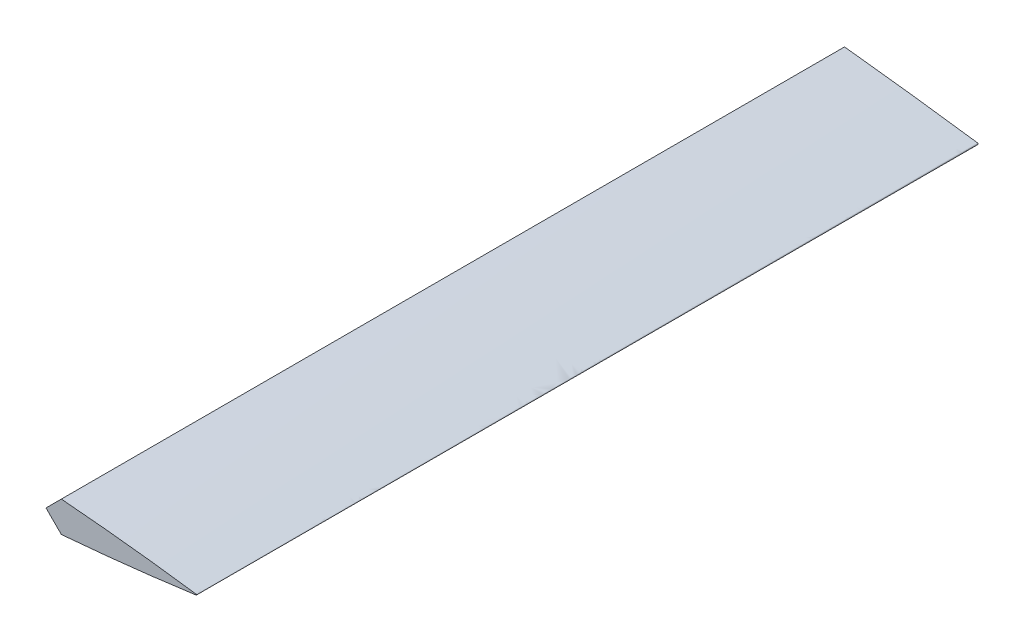
SolidWorks part; units mm, degrees
ref_plane "Front Plane" through (0, 0, 0) normal (1, 0, 0) x (0, 1, 0)
ref_plane "Top Plane" through (0, 0, 0) normal (0, 0, 1) x (0, 1, 0)
ref_plane "Right Plane" through (0, 0, 0) normal (0, 1, 0) x (-1, 0, 0)
curve "Curve1"
  spline degree 3 poles (120, 0.1512, 0) (119.9384, 0.1598, 0) (119.6921, 0.1944, 0) (119.1396, 0.2714, 0) (118.2224, 0.3987, 0) (116.9463, 0.5734, 0) (115.3191, 0.7934, 0) (113.3509, 1.0543, 0) (111.0537, 1.3526, 0) (108.4418, 1.6836, 0) (105.5312, 2.0429, 0) (102.3399, 2.4251, 0) (98.8876, 2.8257, 0) (95.1955, 3.2391, 0) (91.2864, 3.6604, 0) (87.1844, 4.0843, 0) (82.9149, 4.5053, 0) (78.504, 4.9175, 0) (73.9791, 5.3155, 0) (69.368, 5.6926, 0) (64.6991, 6.0428, 0) (60.0013, 6.3594, 0) (55.3033, 6.6359, 0) (50.6343, 6.8653, 0) (46.023, 7.0415, 0) (41.4977, 7.1587, 0) (37.0863, 7.2112, 0) (32.8161, 7.1949, 0) (28.7132, 7.1065, 0) (24.8031, 6.9438, 0) (21.1096, 6.7064, 0) (17.6556, 6.3951, 0) (14.4622, 6.0122, 0) (11.5488, 5.561, 0) (8.9331, 5.0463, 0) (6.6304, 4.4738, 0) (4.6538, 3.8491, 0) (3.0134, 3.1781, 0) (1.7143, 2.4652, 0) (0.7586, 1.7091, 0) (0.1465, 0.8915, 0) (-0.0683, 0, 0) (0.1465, -0.8915, 0) (0.7586, -1.7091, 0) (1.7143, -2.4652, 0) (3.0134, -3.1781, 0) (4.6538, -3.8491, 0) (6.6304, -4.4738, 0) (8.9331, -5.0463, 0) (11.5488, -5.561, 0) (14.4622, -6.0122, 0) (17.6556, -6.3951, 0) (21.1096, -6.7064, 0) (24.8031, -6.9438, 0) (28.7132, -7.1065, 0) (32.8161, -7.1949, 0) (37.0863, -7.2112, 0) (41.4977, -7.1587, 0) (46.023, -7.0415, 0) (50.6343, -6.8653, 0) (55.3033, -6.6359, 0) (60.0013, -6.3594, 0) (64.6991, -6.0428, 0) (69.368, -5.6926, 0) (73.9791, -5.3155, 0) (78.504, -4.9175, 0) (82.9149, -4.5053, 0) (87.1844, -4.0843, 0) (91.2864, -3.6604, 0) (95.1955, -3.2391, 0) (98.8876, -2.8257, 0) (102.3399, -2.4251, 0) (105.5312, -2.0429, 0) (108.4418, -1.6836, 0) (111.0537, -1.3526, 0) (113.3509, -1.0543, 0) (115.3191, -0.7934, 0) (116.9463, -0.5734, 0) (118.2224, -0.3987, 0) (119.1396, -0.2714, 0) (119.6921, -0.1944, 0) (119.9384, -0.1598, 0) (120, -0.1512, 0) knots 0 0 0 0 0.000763 0.003048 0.006841 0.012116 0.018841 0.026973 0.03646 0.047243 0.059254 0.072417 0.086651 0.101866 0.117969 0.134858 0.152428 0.170572 0.189175 0.208122 0.227297 0.24658 0.265853 0.284997 0.303895 0.322433 0.340499 0.357984 0.374788 0.390812 0.405965 0.420162 0.433328 0.445394 0.456301 0.466004 0.474472 0.481696 0.487704 0.492583 0.496544 0.5 0.503456 0.507417 0.512296 0.518304 0.525528 0.533996 0.543699 0.554606 0.566672 0.579838 0.594035 0.609188 0.625212 0.642016 0.659501 0.677567 0.696105 0.715003 0.734147 0.75342 0.772703 0.791878 0.810825 0.829428 0.847572 0.865142 0.882031 0.898134 0.913349 0.927583 0.940746 0.952757 0.96354 0.973027 0.981159 0.987884 0.993159 0.996952 0.999237 1 1 1 1
curve "Curve2"
  spline degree 3 poles (60, 0.0756, 0) (59.9883, 0.0772, 0) (59.9416, 0.0838, 0) (59.8367, 0.0985, 0) (59.6621, 0.1229, 0) (59.4182, 0.1568, 0) (59.1056, 0.2, 0) (58.725, 0.2522, 0) (58.2774, 0.3132, 0) (57.7637, 0.3825, 0) (57.1851, 0.4596, 0) (56.5431, 0.5442, 0) (55.839, 0.6357, 0) (55.0747, 0.7337, 0) (54.2517, 0.8375, 0) (53.3721, 0.9467, 0) (52.438, 1.0606, 0) (51.4514, 1.1787, 0) (50.4147, 1.3003, 0) (49.3304, 1.425, 0) (48.2009, 1.5521, 0) (47.0288, 1.6809, 0) (45.8171, 1.8109, 0) (44.5683, 1.9415, 0) (43.2856, 2.072, 0) (41.9718, 2.2018, 0) (40.6301, 2.3301, 0) (39.2635, 2.4565, 0) (37.8753, 2.58, 0) (36.4687, 2.7001, 0) (35.047, 2.816, 0) (33.6135, 2.927, 0) (32.1716, 3.0322, 0) (30.7246, 3.131, 0) (29.2759, 3.2225, 0) (27.8289, 3.3059, 0) (26.3869, 3.3806, 0) (24.9534, 3.4457, 0) (23.5317, 3.5004, 0) (22.1251, 3.5442, 0) (20.7368, 3.5763, 0) (19.3702, 3.5962, 0) (18.0284, 3.6032, 0) (16.7145, 3.597, 0) (15.4317, 3.5772, 0) (14.1829, 3.5434, 0) (12.971, 3.4956, 0) (11.7988, 3.4335, 0) (10.6691, 3.3571, 0) (9.5846, 3.2667, 0) (8.5477, 3.1624, 0) (7.5609, 3.0445, 0) (6.6264, 2.9134, 0) (5.7465, 2.7696, 0) (4.9231, 2.6137, 0) (4.1582, 2.4461, 0) (3.4535, 2.2677, 0) (2.8107, 2.0791, 0) (2.231, 1.8809, 0) (1.7158, 1.6738, 0) (1.2661, 1.4585, 0) (0.8827, 1.2355, 0) (0.5661, 1.0049, 0) (0.3168, 0.7666, 0) (0.1356, 0.5197, 0) (0.0247, 0.2632, 0) (-0.0121, 0, 0) (0.0247, -0.2632, 0) (0.1356, -0.5197, 0) (0.3168, -0.7666, 0) (0.5661, -1.0049, 0) (0.8827, -1.2355, 0) (1.2661, -1.4585, 0) (1.7158, -1.6738, 0) (2.231, -1.8809, 0) (2.8107, -2.0791, 0) (3.4535, -2.2677, 0) (4.1582, -2.4461, 0) (4.9231, -2.6137, 0) (5.7465, -2.7696, 0) (6.6264, -2.9134, 0) (7.5609, -3.0445, 0) (8.5477, -3.1624, 0) (9.5846, -3.2667, 0) (10.6691, -3.3571, 0) (11.7988, -3.4335, 0) (12.971, -3.4956, 0) (14.1829, -3.5434, 0) (15.4317, -3.5772, 0) (16.7145, -3.597, 0) (18.0284, -3.6032, 0) (19.3702, -3.5962, 0) (20.7368, -3.5763, 0) (22.1251, -3.5442, 0) (23.5317, -3.5004, 0) (24.9534, -3.4457, 0) (26.3869, -3.3806, 0) (27.8289, -3.3059, 0) (29.2759, -3.2225, 0) (30.7246, -3.131, 0) (32.1716, -3.0322, 0) (33.6135, -2.927, 0) (35.047, -2.816, 0) (36.4687, -2.7001, 0) (37.8753, -2.58, 0) (39.2635, -2.4565, 0) (40.6301, -2.3301, 0) (41.9718, -2.2018, 0) (43.2856, -2.072, 0) (44.5683, -1.9415, 0) (45.8171, -1.8109, 0) (47.0288, -1.6809, 0) (48.2009, -1.5521, 0) (49.3304, -1.425, 0) (50.4147, -1.3003, 0) (51.4514, -1.1787, 0) (52.438, -1.0606, 0) (53.3721, -0.9467, 0) (54.2517, -0.8375, 0) (55.0747, -0.7337, 0) (55.839, -0.6357, 0) (56.5431, -0.5442, 0) (57.1851, -0.4596, 0) (57.7637, -0.3825, 0) (58.2774, -0.3132, 0) (58.725, -0.2522, 0) (59.1056, -0.2, 0) (59.4182, -0.1568, 0) (59.6621, -0.1229, 0) (59.8367, -0.0985, 0) (59.9416, -0.0838, 0) (59.9883, -0.0772, 0) (60, -0.0756, 0) knots 0 0 0 0 0.000289 0.001156 0.002598 0.004612 0.007194 0.010336 0.014031 0.018271 0.023046 0.028343 0.03415 0.040454 0.047239 0.054489 0.062186 0.070314 0.078852 0.08778 0.097077 0.106722 0.116691 0.126961 0.137507 0.148306 0.159331 0.170557 0.181957 0.193504 0.205172 0.216932 0.228758 0.240621 0.252495 0.26435 0.276161 0.287898 0.299536 0.311047 0.322405 0.333584 0.344559 0.355306 0.3658 0.376018 0.385938 0.395538 0.404798 0.413699 0.422222 0.430349 0.438066 0.445357 0.452209 0.458611 0.464554 0.47003 0.475035 0.479569 0.483637 0.48725 0.490431 0.493219 0.495674 0.497891 0.5 0.502109 0.504326 0.506781 0.509569 0.51275 0.516363 0.520431 0.524965 0.52997 0.535446 0.541389 0.547791 0.554643 0.561934 0.569651 0.577778 0.586301 0.595202 0.604462 0.614062 0.623982 0.6342 0.644694 0.655441 0.666416 0.677595 0.688953 0.700464 0.712102 0.723839 0.73565 0.747505 0.759379 0.771242 0.783068 0.794828 0.806496 0.818043 0.829443 0.840669 0.851694 0.862493 0.873039 0.883309 0.893278 0.902923 0.91222 0.921148 0.929686 0.937814 0.945511 0.952761 0.959546 0.96585 0.971657 0.976954 0.981729 0.985969 0.989664 0.992806 0.995388 0.997402 0.998844 0.999711 1 1 1 1
sketch "Sketch3" plane through (0, 0, 0) normal (0, 0, 1) x (0, 1, 0)
  arc A0 (-0.1512, -120) -> (0.1512, -120) centre (0, -119.9788) ccw
  spline S0 degree 3 poles (1963.2865, -496.8861) (-12.8593, -186.2558) (-4.4646, -153.1098) (0.2714, -119.1396) (0.3987, -118.2224) (0.5734, -116.9463) (0.7934, -115.3191) (1.0543, -113.3509) (1.3526, -111.0537) (1.6836, -108.4418) (2.0429, -105.5312) (2.4251, -102.3399) (2.8257, -98.8876) (3.2391, -95.1955) (3.6604, -91.2864) (4.0843, -87.1844) (4.5053, -82.9149) (4.9175, -78.504) (5.3155, -73.9791) (5.6926, -69.368) (6.0428, -64.6991) (6.3594, -60.0013) (6.6359, -55.3033) (6.8653, -50.6343) (7.0415, -46.023) (7.1587, -41.4977) (7.2112, -37.0863) (7.1949, -32.8161) (7.1065, -28.7132) (6.9438, -24.8031) (6.7064, -21.1096) (6.3951, -17.6556) (6.0122, -14.4622) (5.561, -11.5488) (5.0463, -8.9331) (4.4738, -6.6304) (3.8491, -4.6538) (3.1781, -3.0134) (2.4652, -1.7143) (1.7091, -0.7586) (0.8915, -0.1465) (0, 0.0683) (-0.8915, -0.1465) (-1.7091, -0.7586) (-2.4652, -1.7143) (-3.1781, -3.0134) (-3.8491, -4.6538) (-4.4738, -6.6304) (-5.0463, -8.9331) (-5.561, -11.5488) (-6.0122, -14.4622) (-6.3951, -17.6556) (-6.7064, -21.1096) (-6.9438, -24.8031) (-7.1065, -28.7132) (-7.1949, -32.8161) (-7.2112, -37.0863) (-7.1587, -41.4977) (-7.0415, -46.023) (-6.8653, -50.6343) (-6.6359, -55.3033) (-6.3594, -60.0013) (-6.0428, -64.6991) (-5.6926, -69.368) (-5.3155, -73.9791) (-4.9175, -78.504) (-4.5053, -82.9149) (-4.0843, -87.1844) (-3.6604, -91.2864) (-3.2391, -95.1955) (-2.8257, -98.8876) (-2.4251, -102.3399) (-2.0429, -105.5312) (-1.6836, -108.4418) (-1.3526, -111.0537) (-1.0543, -113.3509) (-0.7934, -115.3191) (-0.5734, -116.9463) (-0.3987, -118.2224) (-0.2714, -119.1396) (4.4646, -153.1096) (12.8592, -186.2554) (-1963.2505, -496.8804) knots -0.413697 -0.413697 -0.413697 -0.413697 0.000763 0.003048 0.006841 0.012116 0.018841 0.026973 0.03646 0.047243 0.059254 0.072417 0.086651 0.101866 0.117969 0.134858 0.152428 0.170572 0.189175 0.208122 0.227297 0.24658 0.265853 0.284997 0.303895 0.322433 0.340499 0.357984 0.374788 0.390812 0.405965 0.420162 0.433328 0.445394 0.456301 0.466004 0.474472 0.481696 0.487704 0.492583 0.496544 0.5 0.503456 0.507417 0.512296 0.518304 0.525528 0.533996 0.543699 0.554606 0.566672 0.579838 0.594035 0.609188 0.625212 0.642016 0.659501 0.677567 0.696105 0.715003 0.734147 0.75342 0.772703 0.791878 0.810825 0.829428 0.847572 0.865142 0.882031 0.898134 0.913349 0.927583 0.940746 0.952757 0.96354 0.973027 0.981159 0.987884 0.993159 0.996952 0.999237 1.413694 1.413694 1.413694 1.413694 only from (0.1512, -120) to (-0.1512, -120) construction
  spline S1 degree 3 poles (0.1512, -120) (0.1598, -119.9384) (0.1944, -119.6921) (0.2714, -119.1396) (0.3987, -118.2224) (0.5734, -116.9463) (0.7934, -115.3191) (1.0543, -113.3509) (1.3526, -111.0537) (1.6836, -108.4418) (2.0429, -105.5312) (2.4251, -102.3399) (2.8257, -98.8876) (3.2391, -95.1955) (3.6604, -91.2864) (4.0843, -87.1844) (4.5053, -82.9149) (4.9175, -78.504) (5.3155, -73.9791) (5.6926, -69.368) (6.0428, -64.6991) (6.3594, -60.0013) (6.6359, -55.3033) (6.8653, -50.6343) (7.0415, -46.023) (7.1587, -41.4977) (7.2112, -37.0863) (7.1949, -32.8161) (7.1065, -28.7132) (6.9438, -24.8031) (6.7064, -21.1096) (6.3951, -17.6556) (6.0122, -14.4622) (5.561, -11.5488) (5.0463, -8.9331) (4.4738, -6.6304) (3.8491, -4.6538) (3.1781, -3.0134) (2.4652, -1.7143) (1.7091, -0.7586) (0.8915, -0.1465) (0, 0.0683) (-0.8915, -0.1465) (-1.7091, -0.7586) (-2.4652, -1.7143) (-3.1781, -3.0134) (-3.8491, -4.6538) (-4.4738, -6.6304) (-5.0463, -8.9331) (-5.561, -11.5488) (-6.0122, -14.4622) (-6.3951, -17.6556) (-6.7064, -21.1096) (-6.9438, -24.8031) (-7.1065, -28.7132) (-7.1949, -32.8161) (-7.2112, -37.0863) (-7.1587, -41.4977) (-7.0415, -46.023) (-6.8653, -50.6343) (-6.6359, -55.3033) (-6.3594, -60.0013) (-6.0428, -64.6991) (-5.6926, -69.368) (-5.3155, -73.9791) (-4.9175, -78.504) (-4.5053, -82.9149) (-4.0843, -87.1844) (-3.6604, -91.2864) (-3.2391, -95.1955) (-2.8257, -98.8876) (-2.4251, -102.3399) (-2.0429, -105.5312) (-1.6836, -108.4418) (-1.3526, -111.0537) (-1.0543, -113.3509) (-0.7934, -115.3191) (-0.5734, -116.9463) (-0.3987, -118.2224) (-0.2714, -119.1396) (-0.1944, -119.6921) (-0.1598, -119.9384) (-0.1512, -120) knots 0 0 0 0 0.000763 0.003048 0.006841 0.012116 0.018841 0.026973 0.03646 0.047243 0.059254 0.072417 0.086651 0.101866 0.117969 0.134858 0.152428 0.170572 0.189175 0.208122 0.227297 0.24658 0.265853 0.284997 0.303895 0.322433 0.340499 0.357984 0.374788 0.390812 0.405965 0.420162 0.433328 0.445394 0.456301 0.466004 0.474472 0.481696 0.487704 0.492583 0.496544 0.5 0.503456 0.507417 0.512296 0.518304 0.525528 0.533996 0.543699 0.554606 0.566672 0.579838 0.594035 0.609188 0.625212 0.642016 0.659501 0.677567 0.696105 0.715003 0.734147 0.75342 0.772703 0.791878 0.810825 0.829428 0.847572 0.865142 0.882031 0.898134 0.913349 0.927583 0.940746 0.952757 0.96354 0.973027 0.981159 0.987884 0.993159 0.996952 0.999237 1 1 1 1
ref_plane "Plane2" through (0, 0, 140) normal (0, 0, 1) x (0, 1, 0)
sketch "Sketch4" plane through (0, 0, 140) normal (0, 0, 1) x (0, 1, 0)
  arc A4 (-0.0756, -119.9894) -> (0.0756, -119.9894) centre (0, -119.9788) ccw
  spline S2 degree 3 poles (0.0756, -119.9894) (0.0772, -119.9778) (0.0837, -119.9311) (0.0984, -119.8261) (0.1228, -119.6515) (0.1951, -119.1314) (0.282, -118.4981) (0.3824, -117.7531) (0.4596, -117.1746) (0.5442, -116.5325) (0.6357, -115.8285) (0.7336, -115.0641) (0.8375, -114.2412) (1.0752, -112.3257) (1.3139, -110.3072) (1.552, -108.1903) (1.7266, -106.602) (1.9003, -104.9623) (2.1175, -102.8277) (2.3346, -100.5953) (2.541, -98.3209) (2.7409, -95.9803) (2.8923, -94.0775) (3.0322, -92.161) (3.1309, -90.714) (3.2224, -89.2653) (3.3059, -87.8183) (3.3805, -86.3764) (3.4456, -84.9429) (3.5004, -83.5211) (3.5442, -82.1145) (3.5763, -80.7263) (3.5961, -79.3596) (3.6032, -78.0178) (3.597, -76.704) (3.5772, -75.4211) (3.5434, -74.1723) (3.4955, -72.9604) (3.4334, -71.7882) (3.3571, -70.6586) (3.2667, -69.574) (3.1624, -68.5371) (3.0445, -67.5503) (2.9134, -66.6159) (2.7696, -65.7359) (2.6136, -64.9126) (2.4461, -64.1477) (2.2677, -63.443) (2.079, -62.8001) (1.8808, -62.2204) (1.6738, -61.7052) (1.4585, -61.2555) (1.2354, -60.8721) (1.0048, -60.5555) (0.7665, -60.3062) (0.5197, -60.125) (0.2632, -60.0142) (0, -59.9774) (-0.2633, -60.0142) (-0.5198, -60.125) (-0.7666, -60.3062) (-1.0049, -60.5555) (-1.2355, -60.8721) (-1.4586, -61.2555) (-1.6739, -61.7052) (-1.8809, -62.2204) (-2.0791, -62.8001) (-2.2678, -63.443) (-2.4462, -64.1477) (-2.6137, -64.9126) (-2.7697, -65.7359) (-2.9135, -66.6159) (-3.0446, -67.5503) (-3.1625, -68.5371) (-3.2668, -69.574) (-3.3572, -70.6586) (-3.4335, -71.7882) (-3.4956, -72.9604) (-3.5435, -74.1723) (-3.5773, -75.4211) (-3.5971, -76.704) (-3.6033, -78.0178) (-3.5962, -79.3596) (-3.5764, -80.7263) (-3.5442, -82.1145) (-3.5005, -83.5211) (-3.4457, -84.9429) (-3.3806, -86.3764) (-3.306, -87.8183) (-3.2225, -89.2653) (-3.131, -90.714) (-3.0323, -92.161) (-2.8924, -94.0775) (-2.741, -95.9803) (-2.5411, -98.3209) (-2.3346, -100.5953) (-2.077, -103.2446) (-1.8569, -105.3788) (-1.681, -107.0183) (-1.5521, -108.1903) (-1.314, -110.3072) (-1.0752, -112.3257) (-0.8375, -114.2412) (-0.7337, -115.0641) (-0.6358, -115.8285) (-0.5442, -116.5325) (-0.4597, -117.1746) (-0.3456, -118.0295) (-0.2444, -118.7744) (-0.1568, -119.4076) (-0.1229, -119.6515) (-0.0985, -119.8261) (-0.0838, -119.9311) (-0.0773, -119.9778) (-0.0756, -119.9894) knots 0 0 0 0 0.000289 0.001156 0.002598 0.004612 0.014031 0.018271 0.023046 0.028343 0.03415 0.040454 0.047239 0.054489 0.08778 0.097077 0.106722 0.126961 0.137507 0.159331 0.181957 0.193504 0.216932 0.228758 0.240621 0.252495 0.26435 0.276161 0.287898 0.299536 0.311047 0.322405 0.333584 0.344559 0.355306 0.3658 0.376018 0.385938 0.395538 0.404798 0.413699 0.422222 0.430349 0.438066 0.445357 0.452209 0.458611 0.464554 0.47003 0.475035 0.479569 0.483637 0.48725 0.490431 0.493219 0.495674 0.497891 0.5 0.502109 0.504326 0.506781 0.509569 0.51275 0.516363 0.520431 0.524965 0.52997 0.535446 0.541389 0.547791 0.554643 0.561934 0.569651 0.577778 0.586301 0.595202 0.604462 0.614062 0.623982 0.6342 0.644694 0.655441 0.666416 0.677595 0.688953 0.700464 0.712102 0.723839 0.73565 0.747505 0.759379 0.771242 0.783068 0.806496 0.818043 0.840669 0.862493 0.883309 0.893278 0.902923 0.91222 0.945511 0.952761 0.959546 0.96585 0.971657 0.976954 0.981729 0.992806 0.995388 0.997402 0.998844 0.999711 1 1 1 1
loft "Loft1" add profiles "Sketch3", "Sketch4"
sketch "Sketch5" plane through (0, 0, 0) normal (0, 0, -1) x (1, 0, 0)
  circle A0 centre (59.9788, 0) radius 3.175
  arc A2 (120, -0.1512) -> (120, 0.1512) centre (119.9788, 0) ccw
  arc A3 (120, -0.1512) -> (120, 0.1512) centre (119.9788, 0) ccw
  spline S2 degree 3 poles (2119.9475, -2119.2172) (88.467, 73.5642) (-7.4592, 9.2673) (0.7585, -1.7091) (1.7141, -2.4652) (3.0132, -3.1781) (4.6536, -3.8491) (6.6302, -4.4738) (8.9329, -5.0463) (11.5486, -5.5611) (14.4621, -6.0122) (17.6555, -6.3951) (21.1095, -6.7064) (24.803, -6.9438) (28.7131, -7.1065) (32.816, -7.1949) (37.0862, -7.2112) (41.4976, -7.1587) (46.0229, -7.0415) (50.6342, -6.8653) (55.3033, -6.6359) (60.0012, -6.3594) (64.6991, -6.0428) (69.368, -5.6926) (73.9791, -5.3155) (78.504, -4.9175) (82.9148, -4.5053) (87.1844, -4.0843) (91.2864, -3.6604) (95.1955, -3.2392) (98.8876, -2.8257) (102.3399, -2.4251) (105.5312, -2.0429) (108.4418, -1.6836) (111.0537, -1.3526) (113.3509, -1.0543) (115.3191, -0.7934) (116.9463, -0.5734) (118.2224, -0.3987) (119.1396, -0.2714) (157.9529, 5.1398) (195.7823, 15.3513) (649.9649, -2951.4825) knots -0.152784 -0.152784 -0.152784 -0.152784 0.003456 0.007417 0.012296 0.018304 0.025528 0.033996 0.043699 0.054606 0.066672 0.079838 0.094035 0.109188 0.125212 0.142016 0.159501 0.177567 0.196105 0.215003 0.234147 0.25342 0.272703 0.291878 0.310825 0.329428 0.347572 0.365142 0.382031 0.398134 0.413349 0.427583 0.440746 0.452757 0.46354 0.473027 0.481159 0.487884 0.493159 0.496952 0.499237 0.973652 0.973652 0.973652 0.973652 only from (-0.0002, 0) to (120, -0.1512)
  spline S3 degree 3 poles (461.0436, -2895.7858) (729.0476, -278.0991) (431.132, -38.6969) (104.835, 2.1364) (97.239, 3.0204) (90.903, 3.7041) (84.5629, 4.3482) (79.4875, 4.8306) (74.409, 5.2774) (70.5984, 5.5933) (66.7862, 5.8885) (62.9723, 6.1614) (59.1567, 6.4099) (55.3395, 6.6314) (51.5206, 6.8228) (47.7002, 6.9808) (43.8784, 7.1016) (40.0556, 7.1802) (36.232, 7.211) (33.0456, 7.1913) (30.4969, 7.1443) (28.5858, 7.092) (26.6753, 7.0215) (24.7656, 6.931) (22.857, 6.819) (20.95, 6.683) (19.045, 6.5208) (17.1428, 6.3292) (15.2441, 6.1046) (13.3503, 5.8421) (11.7776, 5.5867) (10.524, 5.3562) (9.5866, 5.1687) (8.6527, 4.965) (7.7227, 4.7434) (6.7981, 4.5007) (5.8799, 4.2344) (4.9705, 3.9393) (4.0729, 3.6103) (3.1916, 3.2386) (2.3358, 2.8121) (1.5185, 2.3128) (0.7755, 1.7074) (-7.7702, -9.0011) (82.4901, -76.2927) (2232.3644, 1999.1772) knots -3.429668 -3.429668 -3.429668 -3.429668 0.532086 0.56328 0.594474 0.625669 0.641266 0.67246 0.688057 0.703654 0.719251 0.734849 0.750446 0.766043 0.78164 0.797237 0.812834 0.828431 0.844029 0.859626 0.867424 0.875223 0.883021 0.89082 0.898619 0.906417 0.914216 0.922014 0.929813 0.937611 0.94541 0.949309 0.953209 0.957108 0.961007 0.964906 0.968806 0.972705 0.976604 0.980504 0.984403 0.988302 0.992201 0.996101 1.154232 1.154232 1.154232 1.154232 only from (120, 0.1512) to (-0.0002, 0)
  spline S4 degree 3 poles (-0.0002, 0) (-0.0002, -0.2834) (0.1464, -0.8915) (0.7585, -1.7091) (1.7141, -2.4652) (3.0132, -3.1781) (4.6536, -3.8491) (6.6302, -4.4738) (8.9329, -5.0463) (11.5486, -5.5611) (14.4621, -6.0122) (17.6555, -6.3951) (21.1095, -6.7064) (24.803, -6.9438) (28.7131, -7.1065) (32.816, -7.1949) (37.0862, -7.2112) (41.4976, -7.1587) (46.0229, -7.0415) (50.6342, -6.8653) (55.3033, -6.6359) (60.0012, -6.3594) (64.6991, -6.0428) (69.368, -5.6926) (73.9791, -5.3155) (78.504, -4.9175) (82.9148, -4.5053) (87.1844, -4.0843) (91.2864, -3.6604) (95.1955, -3.2392) (98.8876, -2.8257) (102.3399, -2.4251) (105.5312, -2.0429) (108.4418, -1.6836) (111.0537, -1.3526) (113.3509, -1.0543) (115.3191, -0.7934) (116.9463, -0.5734) (118.2224, -0.3987) (119.1396, -0.2714) (119.6921, -0.1944) (119.9384, -0.1598) (120, -0.1512) knots 0 0 0 0 0.003456 0.007417 0.012296 0.018304 0.025528 0.033996 0.043699 0.054606 0.066672 0.079838 0.094035 0.109188 0.125212 0.142016 0.159501 0.177567 0.196105 0.215003 0.234147 0.25342 0.272703 0.291878 0.310825 0.329428 0.347572 0.365142 0.382031 0.398134 0.413349 0.427583 0.440746 0.452757 0.46354 0.473027 0.481159 0.487884 0.493159 0.496952 0.499237 0.5 0.5 0.5 0.5
  spline S5 degree 3 poles (120, 0.1512) (117.4756, 0.5052) (112.4232, 1.1868) (104.835, 2.1364) (97.239, 3.0204) (90.903, 3.7041) (84.5629, 4.3482) (79.4875, 4.8306) (74.409, 5.2774) (70.5984, 5.5933) (66.7862, 5.8885) (62.9723, 6.1614) (59.1567, 6.4099) (55.3395, 6.6314) (51.5206, 6.8228) (47.7002, 6.9808) (43.8784, 7.1016) (40.0556, 7.1802) (36.232, 7.211) (33.0456, 7.1913) (30.4969, 7.1443) (28.5858, 7.092) (26.6753, 7.0215) (24.7656, 6.931) (22.857, 6.819) (20.95, 6.683) (19.045, 6.5208) (17.1428, 6.3292) (15.2441, 6.1046) (13.3503, 5.8421) (11.7776, 5.5867) (10.524, 5.3562) (9.5866, 5.1687) (8.6527, 4.965) (7.7227, 4.7434) (6.7981, 4.5007) (5.8799, 4.2344) (4.9705, 3.9393) (4.0729, 3.6103) (3.1916, 3.2386) (2.3358, 2.8121) (1.5185, 2.3128) (0.7755, 1.7074) (0.1731, 0.9524) (-0.0002, 0.3175) (-0.0002, 0) knots 0.500891 0.500891 0.500891 0.500891 0.532086 0.56328 0.594474 0.625669 0.641266 0.67246 0.688057 0.703654 0.719251 0.734849 0.750446 0.766043 0.78164 0.797237 0.812834 0.828431 0.844029 0.859626 0.867424 0.875223 0.883021 0.89082 0.898619 0.906417 0.914216 0.922014 0.929813 0.937611 0.94541 0.949309 0.953209 0.957108 0.961007 0.964906 0.968806 0.972705 0.976604 0.980504 0.984403 0.988302 0.992201 0.996101 1 1 1 1
  dimension "D1" = 6.35
  dimension "D3" = 60
  dimension "D2" = 0
extrude "Cut-Extrude1" cut sketch "Sketch5" against normal blind 40 contours A0
sketch "Sketch6" plane through (0, 0, 0) normal (0, 1, 0) x (-1, 0, 0)
  line L0 (-59.9889, 140) -> (-119.9894, 140) construction
  line L1 (-121.585, 0) -> (-93.085, 0)
  line L2 (-121.585, 0) -> (-121.585, 140)
  line L3 (-121.585, 140) -> (-93.085, 140)
  line L4 (-93.085, 0) -> (-93.085, 140)
  line L6 (0, 0) -> (-93.085, 0)
  line L7 (0, 0) -> (0, 140)
  line L8 (0, 140) -> (-93.085, 140)
  line L9 (-93.085, 0) -> (-93.085, 140)
  dimension "D1" = 140
  dimension "D2" = 28.5
extrude "Cut-Extrude4" cut sketch "Sketch6" against normal through all both and the other way through all contours L7 L6 L9 L8
sketch "Sketch8" plane through (0, 0, 140) normal (0, 0, 1) x (1, 0, 0)
  line L0 (93.085, 0) -> (93.085, 8.938)
  line L1 (93.085, -2.9647) -> (93.085, 2.9646) construction
  line L2 (93.085, 8.938) -> (102.023, 8.938)
  line L3 (102.023, 8.938) -> (93.085, 0)
  line L4 (93.085, 0) -> (93.085, -8.9962)
  line L5 (93.085, -8.9962) -> (102.0812, -8.9962)
  line L6 (102.0812, -8.9962) -> (93.085, 0)
  dimension "D1" = 45
  dimension "D2" = 45
extrude "Cut-Extrude5" cut sketch "Sketch8" against normal through all both and the other way through all contours L3 L0 L2 | L4 L5 L6
